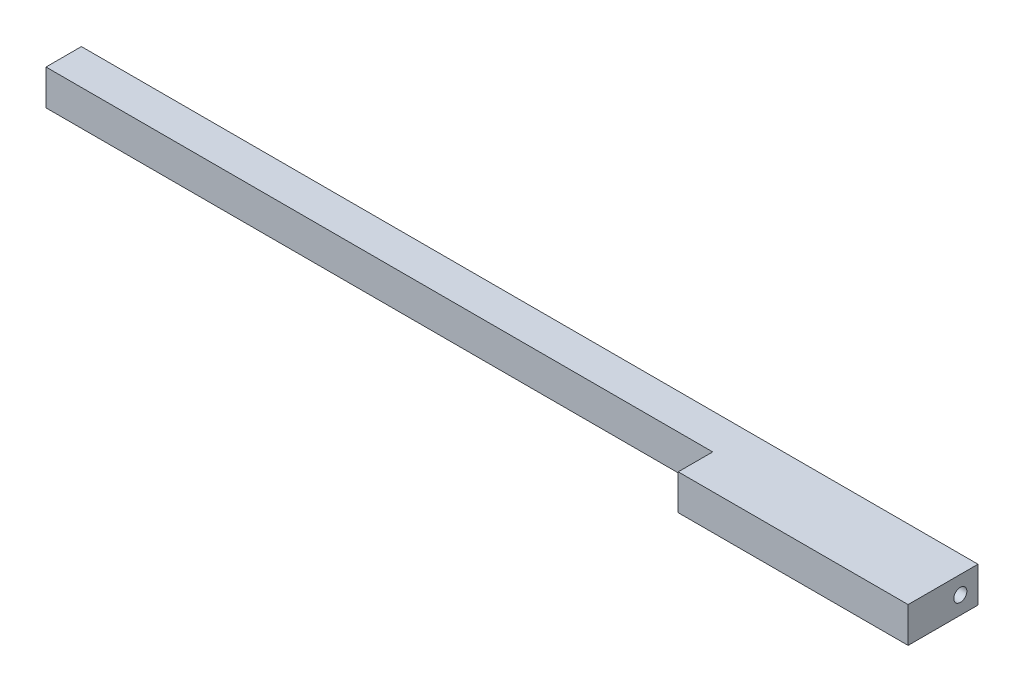
SolidWorks part; units mm, degrees
ref_plane "Front Plane" through (0, 0, 0) normal (0, 0, 1) x (1, 0, 0)
ref_plane "Top Plane" through (0, 0, 0) normal (0, 1, 0) x (1, 0, 0)
ref_plane "Right Plane" through (0, 0, 0) normal (1, 0, 0) x (0, 0, -1)
sketch "Sketch1" plane through (-17.272, 0, 0) normal (-1, 0, 0) x (0, 0, 1)
  line L1 (34.671, 91.821) -> (54.229, 91.821)
  line L2 (34.671, 91.821) -> (34.671, 111.379)
  line L3 (34.671, 111.379) -> (54.229, 111.379)
  line L4 (54.229, 91.821) -> (54.229, 111.379)
  line L5 (34.671, 91.821) -> (54.229, 111.379) construction
  line L6 (34.671, 111.379) -> (54.229, 91.821) construction
  point P0 (44.45, 101.6)
  dimension "D1" = 19.558
extrude "Boss-Extrude1" add sketch "Sketch1" along normal blind 457.2 and the other way blind 38.1 contours L3 L4 L1 L2
sketch "Sketch2" plane through (20.828, 0, 0) normal (1, 0, 0) x (0, 0, -1)
  circle A0 centre (-44.45, 101.6) radius 3.6195
  dimension "D1" = 7.239
extrude "Cut-Extrude1" cut sketch "Sketch2" against normal blind 38.1 contours A0
sketch "Sketch3" plane through (0, 0, 54.229) normal (0, 0, 1) x (1, 0, 0)
  line L0 (20.828, 91.821) -> (-474.472, 91.821) construction
  line L1 (-106.172, 111.379) -> (20.828, 111.379)
  line L2 (-106.172, 111.379) -> (-106.172, 91.821)
  line L3 (-106.172, 91.821) -> (20.828, 91.821)
  line L4 (20.828, 111.379) -> (20.828, 91.821)
  line L5 (-106.172, 111.379) -> (20.828, 91.821) construction
  line L6 (-106.172, 91.821) -> (20.828, 111.379) construction
  line L7 (20.828, 111.379) -> (-474.472, 111.379) construction
  line L8 (20.828, 91.821) -> (20.828, 111.379) construction
  point P0 (-42.672, 101.6)
  dimension "D1" = 127
extrude "Boss-Extrude2" add sketch "Sketch3" along normal blind 19.05
